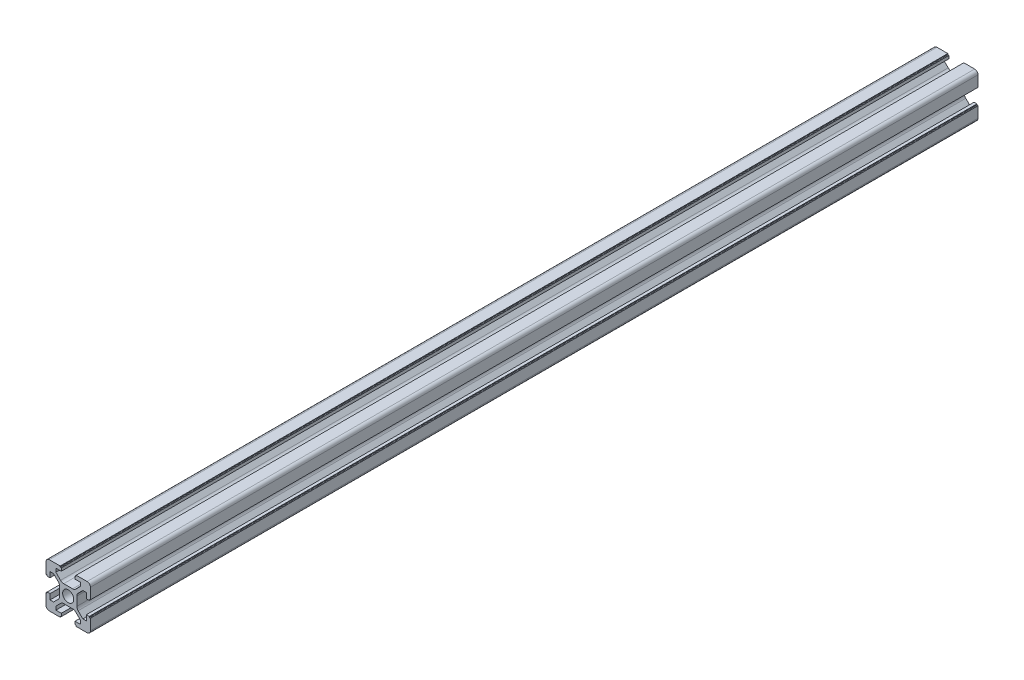
SolidWorks part; units mm, degrees
ref_plane "Спереди" through (0, 0, 0) normal (0, 0, 1) x (1, 0, 0)
ref_plane "Сверху" through (0, 0, 0) normal (0, 1, 0) x (1, 0, 0)
ref_plane "Справа" through (0, 0, 0) normal (1, 0, 0) x (0, 0, -1)
sketch "Sketch1" plane through (0, 0, 0) normal (0, 0, 1) x (1, 0, 0)
  line L0 (0, 10) -> (0, -10) construction
  line L1 (-10, -10) -> (10, -10) construction
  line L2 (-10, -10) -> (-10, 10) construction
  line L3 (-10, 10) -> (10, 10) construction
  line L4 (10, -10) -> (10, 10) construction
  line L5 (-10, -10) -> (10, 10) construction
  line L6 (-10, 10) -> (10, -10) construction
  line L7 (-10, 0) -> (10, 0) construction
  line L8 (0, 3.9) -> (-2.0109, 3.9)
  line L9 (-3.4251, 4.4858) -> (-5.5393, 6.6)
  line L10 (-5.5393, 6.6) -> (-5.5393, 8.2)
  line L11 (-5.5393, 8.2) -> (-3.1, 8.2)
  line L12 (-3.1, 8.2) -> (-3.1, 9.5)
  line L13 (-3.1, 9.5) -> (-3.4, 9.5)
  line L14 (-3.6, 9.7) -> (-3.6, 10)
  line L15 (-3.6, 10) -> (-8.5, 10)
  line L16 (-10, 3.6) -> (-10, 8.5)
  line L17 (-9.7, 3.6) -> (-10, 3.6)
  line L18 (-9.5, 3.1) -> (-9.5, 3.4)
  line L19 (-8.2, 3.1) -> (-9.5, 3.1)
  line L20 (-8.2, 5.5393) -> (-8.2, 3.1)
  line L21 (-6.6, 5.5393) -> (-8.2, 5.5393)
  line L22 (-4.4858, 3.4251) -> (-6.6, 5.5393)
  line L23 (-3.9, 0) -> (-3.9, 2.0109)
  line L24 (3.9, 0) -> (3.9, 2.0109)
  line L25 (4.4858, 3.4251) -> (6.6, 5.5393)
  line L26 (6.6, 5.5393) -> (8.2, 5.5393)
  line L27 (8.2, 5.5393) -> (8.2, 3.1)
  line L28 (8.2, 3.1) -> (9.5, 3.1)
  line L29 (9.5, 3.1) -> (9.5, 3.4)
  line L30 (9.7, 3.6) -> (10, 3.6)
  line L31 (10, 3.6) -> (10, 8.5)
  line L32 (3.6, 10) -> (8.5, 10)
  line L33 (3.6, 9.7) -> (3.6, 10)
  line L34 (3.1, 9.5) -> (3.4, 9.5)
  line L35 (3.1, 8.2) -> (3.1, 9.5)
  line L36 (5.5393, 8.2) -> (3.1, 8.2)
  line L37 (5.5393, 6.6) -> (5.5393, 8.2)
  line L38 (3.4251, 4.4858) -> (5.5393, 6.6)
  line L39 (0, 3.9) -> (2.0109, 3.9)
  line L40 (0, -3.9) -> (2.0109, -3.9)
  line L41 (3.4251, -4.4858) -> (5.5393, -6.6)
  line L42 (5.5393, -6.6) -> (5.5393, -8.2)
  line L43 (5.5393, -8.2) -> (3.1, -8.2)
  line L44 (3.1, -8.2) -> (3.1, -9.5)
  line L45 (3.1, -9.5) -> (3.4, -9.5)
  line L46 (3.6, -9.7) -> (3.6, -10)
  line L47 (3.6, -10) -> (8.5, -10)
  line L48 (10, -3.6) -> (10, -8.5)
  line L49 (9.7, -3.6) -> (10, -3.6)
  line L50 (9.5, -3.1) -> (9.5, -3.4)
  line L51 (8.2, -3.1) -> (9.5, -3.1)
  line L52 (8.2, -5.5393) -> (8.2, -3.1)
  line L53 (6.6, -5.5393) -> (8.2, -5.5393)
  line L54 (4.4858, -3.4251) -> (6.6, -5.5393)
  line L55 (3.9, 0) -> (3.9, -2.0109)
  line L56 (-3.9, 0) -> (-3.9, -2.0109)
  line L57 (-4.4858, -3.4251) -> (-6.6, -5.5393)
  line L58 (-6.6, -5.5393) -> (-8.2, -5.5393)
  line L59 (-8.2, -5.5393) -> (-8.2, -3.1)
  line L60 (-8.2, -3.1) -> (-9.5, -3.1)
  line L61 (-9.5, -3.1) -> (-9.5, -3.4)
  line L62 (-9.7, -3.6) -> (-10, -3.6)
  line L63 (-10, -3.6) -> (-10, -8.5)
  line L64 (-3.6, -10) -> (-8.5, -10)
  line L65 (-3.6, -9.7) -> (-3.6, -10)
  line L66 (-3.1, -9.5) -> (-3.4, -9.5)
  line L67 (-3.1, -8.2) -> (-3.1, -9.5)
  line L68 (-5.5393, -8.2) -> (-3.1, -8.2)
  line L69 (-5.5393, -6.6) -> (-5.5393, -8.2)
  line L70 (-3.4251, -4.4858) -> (-5.5393, -6.6)
  line L71 (0, -3.9) -> (-2.0109, -3.9)
  circle A0 centre (0, 0) radius 2.5
  arc A1 (-8.5, 10) -> (-10, 8.5) centre (-8.5, 8.5) ccw
  arc A2 (-2.0109, 3.9) -> (-3.4251, 4.4858) centre (-2.0109, 5.9) cw
  arc A3 (-3.4, 9.5) -> (-3.6, 9.7) centre (-3.4, 9.7) cw
  arc A4 (-9.5, 3.4) -> (-9.7, 3.6) centre (-9.7, 3.4) ccw
  arc A5 (-3.9, 2.0109) -> (-4.4858, 3.4251) centre (-5.9, 2.0109) ccw
  arc A6 (10, 8.5) -> (8.5, 10) centre (8.5, 8.5) ccw
  arc A7 (3.9, 2.0109) -> (4.4858, 3.4251) centre (5.9, 2.0109) cw
  arc A8 (9.5, 3.4) -> (9.7, 3.6) centre (9.7, 3.4) cw
  arc A9 (3.4, 9.5) -> (3.6, 9.7) centre (3.4, 9.7) ccw
  arc A10 (2.0109, 3.9) -> (3.4251, 4.4858) centre (2.0109, 5.9) ccw
  arc A11 (8.5, -10) -> (10, -8.5) centre (8.5, -8.5) ccw
  arc A12 (2.0109, -3.9) -> (3.4251, -4.4858) centre (2.0109, -5.9) cw
  arc A13 (3.4, -9.5) -> (3.6, -9.7) centre (3.4, -9.7) cw
  arc A14 (9.5, -3.4) -> (9.7, -3.6) centre (9.7, -3.4) ccw
  arc A15 (3.9, -2.0109) -> (4.4858, -3.4251) centre (5.9, -2.0109) ccw
  arc A16 (-10, -8.5) -> (-8.5, -10) centre (-8.5, -8.5) ccw
  arc A17 (-3.9, -2.0109) -> (-4.4858, -3.4251) centre (-5.9, -2.0109) cw
  arc A18 (-9.5, -3.4) -> (-9.7, -3.6) centre (-9.7, -3.4) cw
  arc A19 (-3.4, -9.5) -> (-3.6, -9.7) centre (-3.4, -9.7) ccw
  arc A20 (-2.0109, -3.9) -> (-3.4251, -4.4858) centre (-2.0109, -5.9) ccw
  point P0 (0, 0)
  point P42 (0, 0)
  point P70 (0, 0)
  point P98 (0, 0)
  point P126 (0, 0)
  dimension "D3" = 5
  dimension "D4" = 3
  dimension "D12" = 2
  dimension "D13" = 0.2
  dimension "D1" = 20
  dimension "D2" = 20
  dimension "D5" = 6.2
  dimension "D6" = 7.2
  dimension "D7" = 1.8
  dimension "D8" = 0.5
  dimension "D9" = 3.4
  dimension "D10" = 1.5
  dimension "D11" = 6.1
  dimension "D14" = 4
extrude "Extrude1" add sketch "Sketch1" along normal blind 400
